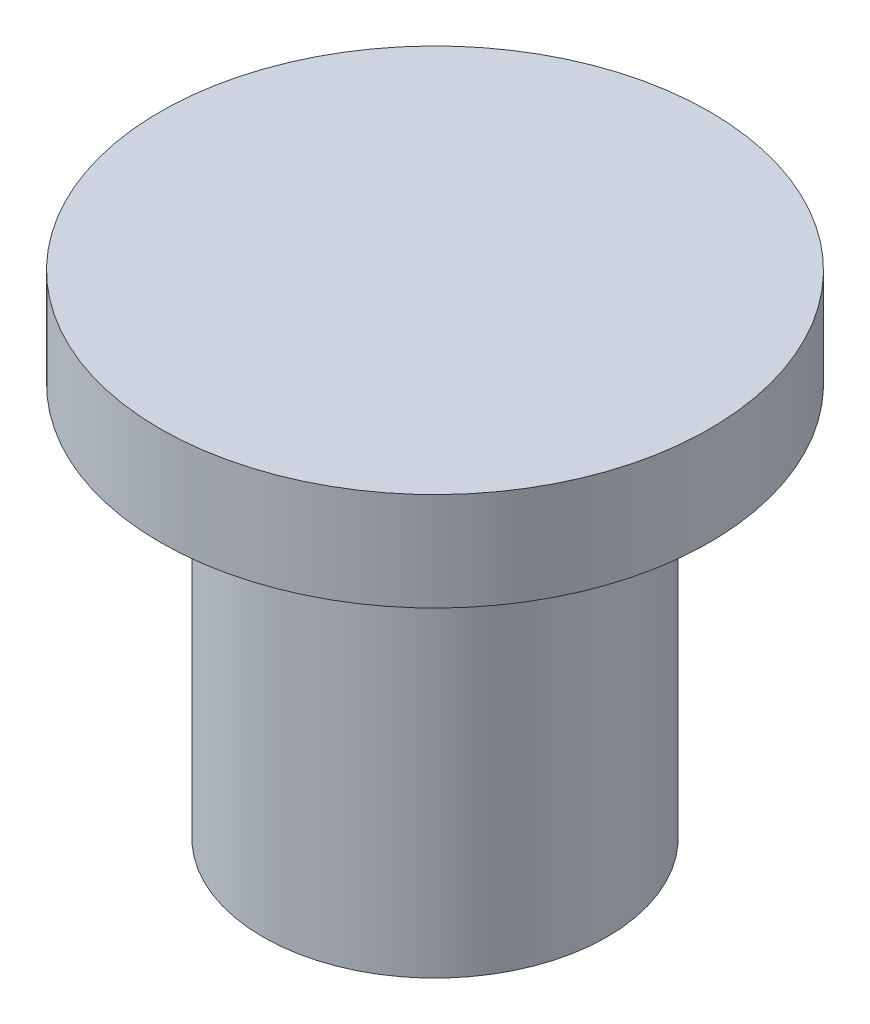
SolidWorks part; units mm, degrees
ref_plane "Plan de face" through (0, 0, 0) normal (0, 0, 1) x (1, 0, 0)
ref_plane "Plan de dessus" through (0, 0, 0) normal (0, 1, 0) x (1, 0, 0)
ref_plane "Plan de droite" through (0, 0, 0) normal (1, 0, 0) x (0, 0, -1)
sketch "Esquisse1" plane through (0, 0, 0) normal (0, 1, 0) x (1, 0, 0)
  circle A0 centre (0, 0) radius 4
  circle A1 centre (0, 0) radius 1.75
extrude "Boss.-Extru.1" add sketch "Esquisse1" against normal blind 4 contours A1
sketch "Esquisse2" plane through (0, 0, 0) normal (0, 1, 0) x (1, 0, 0)
  circle A0 centre (0, 0) radius 2.7953
extrude "Boss.-Extru.2" add sketch "Esquisse2" along normal blind 1
